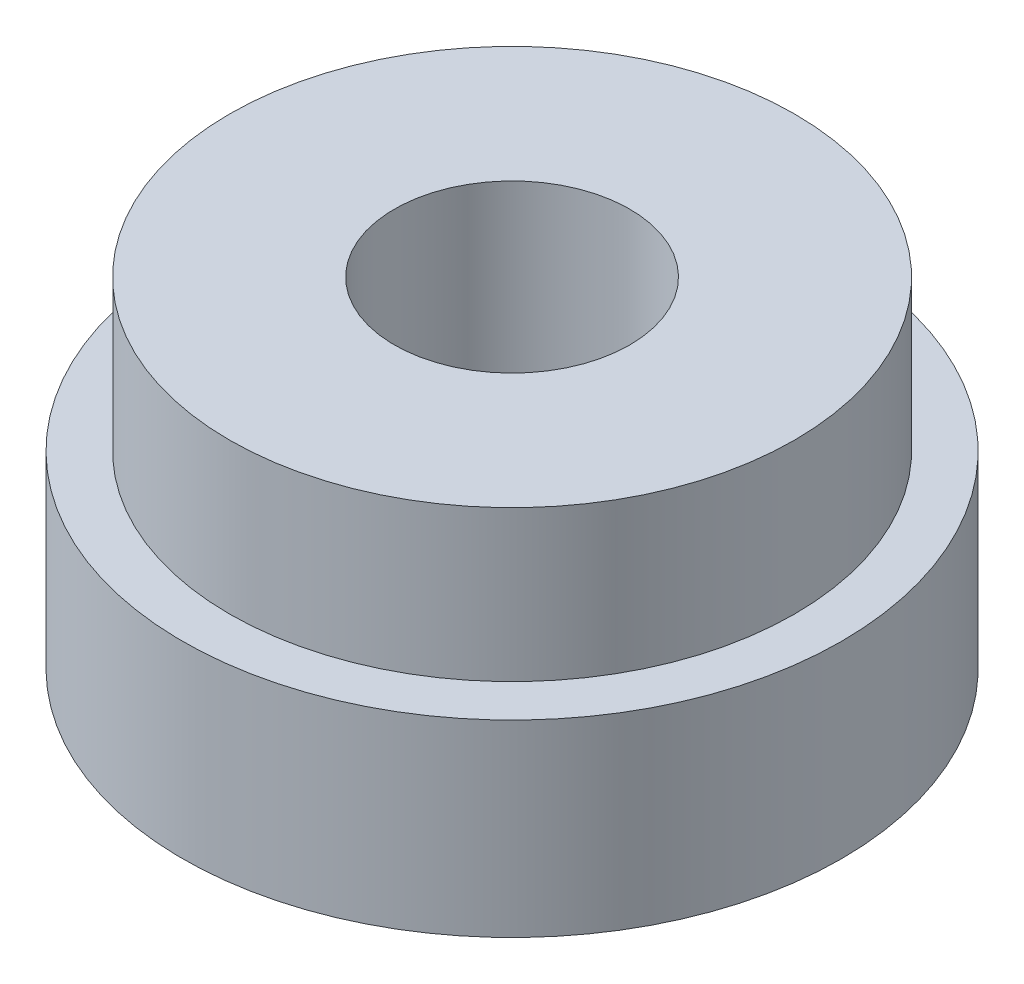
SolidWorks part; units mm, degrees
material "ｱﾙﾐ青銅"
ref_plane "正面" through (0, 0, 0) normal (0, 0, 1) x (1, 0, 0)
ref_plane "平面" through (0, 0, 0) normal (0, 1, 0) x (1, 0, 0)
ref_plane "右側面" through (0, 0, 0) normal (1, 0, 0) x (0, 0, -1)
sketch "ｽｹｯﾁ1" plane through (0, 0, 0) normal (0, 0, 1) x (1, 0, 0)
  line L0 (1.25, 0) -> (1.25, 3.6)
  line L1 (1.25, 3.6) -> (3, 3.6)
  line L2 (3, 3.6) -> (3, 2)
  line L3 (3, 2) -> (3.5, 2)
  line L4 (3.5, 2) -> (3.5, 0)
  line L5 (3.5, 0) -> (1.25, 0)
  line L6 (0, 0) -> (0, 3.6) construction
  dimension "D1" = 3.6
  dimension "D2" = 2
  dimension "D3" = 3.5
  dimension "D4" = 3
  dimension "D5" = 1.25
revolve "回転1" add sketch "ｽｹｯﾁ1" angle 360 about L6
